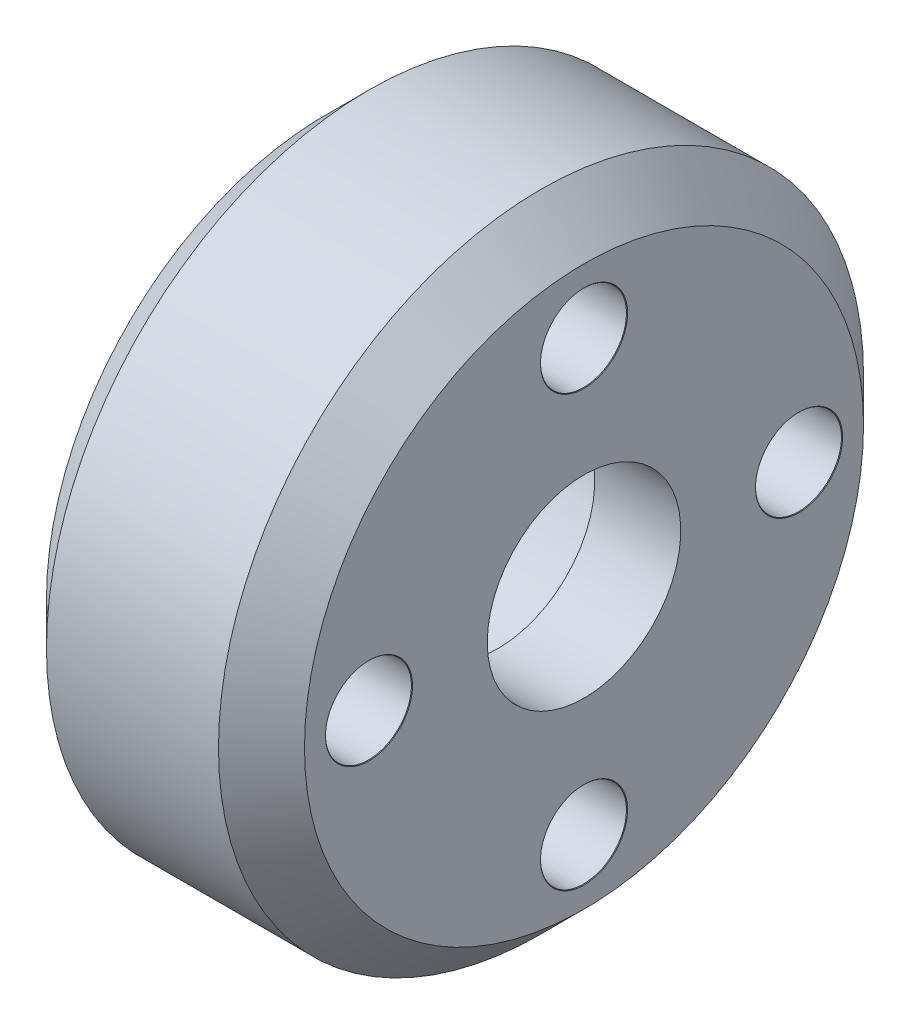
SolidWorks part; units mm, degrees
material "Сталь 40Х ГОСТ 4543-71"
ref_plane "Спереди (Плоскость XY)" through (0, 0, 0) normal (0, 0, 1) x (1, 0, 0)
ref_plane "Сверху (Плоскость XZ)" through (0, 0, 0) normal (0, 1, 0) x (1, 0, 0)
ref_plane "Справа (Плоскость ZY)" through (0, 0, 0) normal (1, 0, 0) x (0, 0, -1)
other "Configuration Table"
sketch "Эскиз1" plane through (0, 0, 0) normal (0, 0, 1) x (1, 0, 0)
  line L0 (0, 0) -> (47.2413, 0) construction
  line L1 (0, 7) -> (0, 15)
  line L2 (0, 15) -> (12, 15)
  line L3 (12, 15) -> (12, 4.5)
  line L5 (0, 7) -> (8, 7)
  line L6 (8, 7) -> (8, 4.5)
  line L7 (8, 4.5) -> (12, 4.5)
  dimension "D1" = 12
  dimension "D3" = 14
  dimension "D4" = 8
  dimension "D5" = 9
  dimension "D6" = 30
revolve "Повернуть1" add sketch "Эскиз1" angle 360 about L0
cosmetic thread "Условное изображение резьбы1" parameters "D1"=11.9999, "D2"=28.344
hole_wizard "Отверстия под штифты Ø4.0 мм1" positions "Эскиз5" profile "Эскиз3" hole size "Ø4.0" standard "DIN"
sketch "Эскиз5" plane through (12, 0, 0) normal (1, 0, 0) x (0, 0, -1)
  point P0 (0, 10)
  dimension "D1" = 10
sketch "Эскиз3" plane through (12, 10, 0) normal (0, 1, 0) x (0, 0, -1)
  line L0 (0, 0) -> (0, 6.2017)
  line L1 (0, 6.2017) -> (2, 5)
  line L2 (2, 5) -> (2, 0.025)
  line L3 (2, 0.025) -> (2.025, 0)
  line L5 (2.025, 0) -> (0, 0)
  line L6 (-2, 0.025) -> (-2.025, 0) construction
  line L10 (0, 6.2017) -> (-2, 5) construction
  line L11 (0, -6.35) -> (0, 107.95) construction
  dimension "Диаметр отверстия" = 4
  dimension "Глубина отверстия" = 5
  dimension "Диаметр передней зенковки" = 4.05
  dimension "Угол передней зенковки" = 90
  dimension "Угол заточки сверла" = 118
pattern_circular "Круговой массив2" count 4 every 90 about axis through (0, 0, 0) along (1, 0, 0) of "Отверстия под штифты Ø4.0 мм1"
chamfer "Фаска1" distance 2 angle 45 2 edges at (0, 0, 15) (12, 0, 15)
